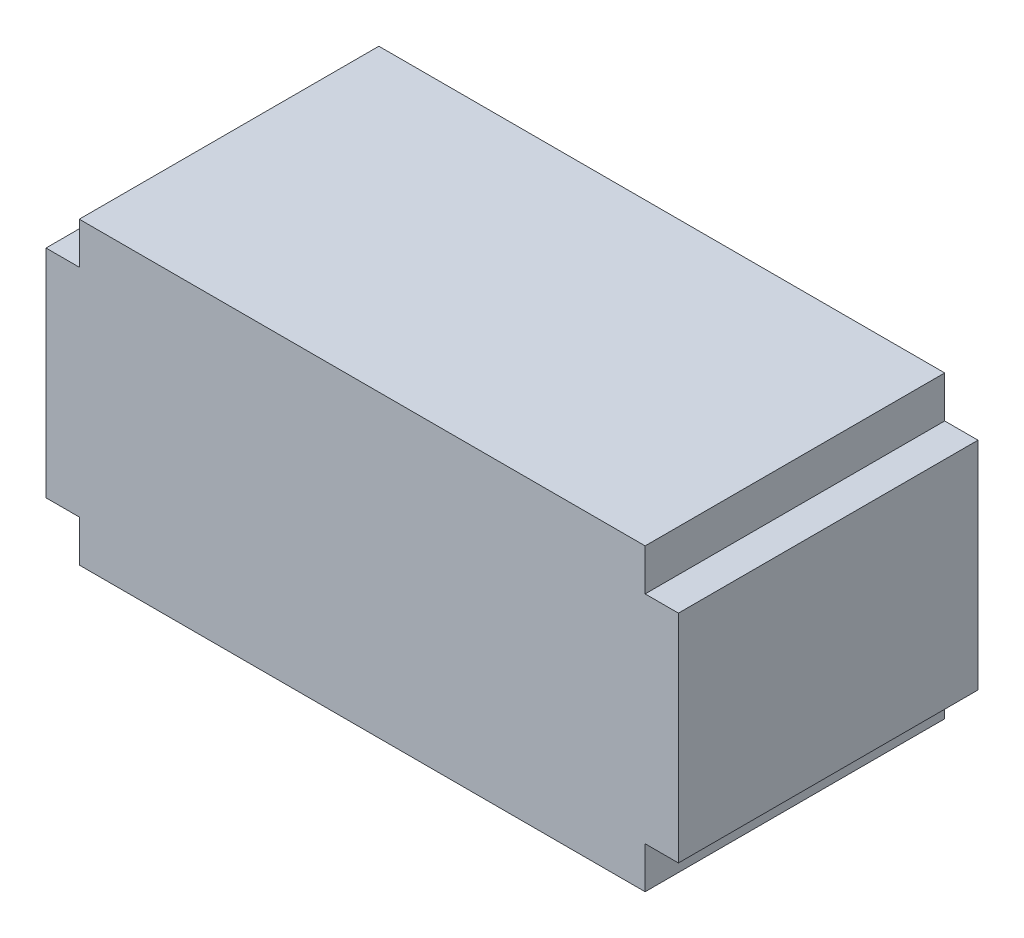
SolidWorks part; units mm, degrees
ref_plane "前视基准面" through (0, 0, 0) normal (0, 0, 1) x (1, 0, 0)
ref_plane "上视基准面" through (0, 0, 0) normal (0, 1, 0) x (1, 0, 0)
ref_plane "右视基准面" through (0, 0, 0) normal (1, 0, 0) x (0, 0, -1)
sketch "草图1" plane through (0, 0, 0) normal (0, 0, 1) x (1, 0, 0)
  line L0 (-1.7, -0.9) -> (-1.7, -0.65)
  line L1 (-1.7, -0.65) -> (-1.9, -0.65)
  line L2 (-1.9, -0.65) -> (-1.9, 0.65)
  line L3 (-1.9, 0.65) -> (-1.7, 0.65)
  line L4 (-1.7, 0.65) -> (-1.7, 0.9)
  line L5 (-1.7, 0.9) -> (1.7, 0.9)
  line L6 (1.7, 0.9) -> (1.7, 0.65)
  line L7 (1.7, 0.65) -> (1.9, 0.65)
  line L8 (1.9, 0.65) -> (1.9, -0.65)
  line L9 (1.9, -0.65) -> (1.7, -0.65)
  line L10 (1.7, -0.65) -> (1.7, -0.9)
  line L11 (1.7, -0.9) -> (-1.7, -0.9)
extrude "Component_Outline" add sketch "草图1" along normal blind 1.8 separate body
sketch3d "3D草图1"
  line L0 (0, 0, 0) -> (1, 0, 0)
  line L1 (0, 0, 0) -> (0, 1, 0)
  line L2 (0, 0, 0) -> (0, 0, 1)
  point P0 (0, 0, 0)
